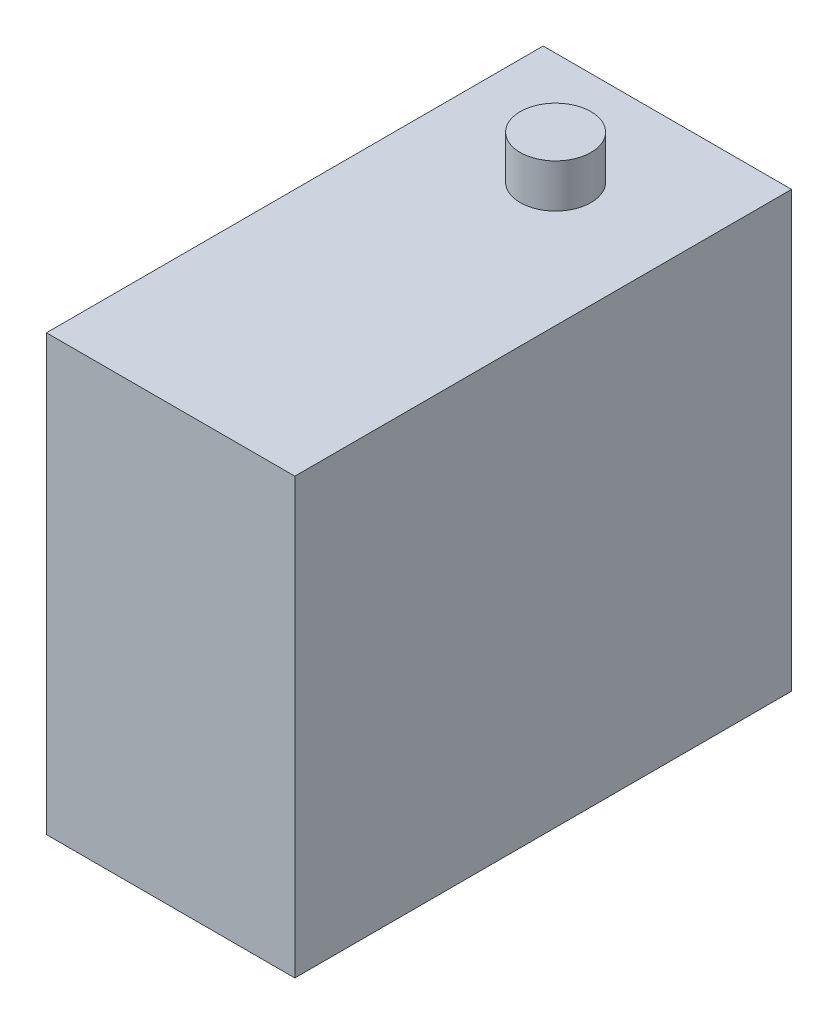
SolidWorks part; units mm, degrees
ref_plane "Front Plane" through (0, 0, 0) normal (0, 0, 1) x (1, 0, 0)
ref_plane "Top Plane" through (0, 0, 0) normal (0, 1, 0) x (1, 0, 0)
ref_plane "Right Plane" through (0, 0, 0) normal (1, 0, 0) x (0, 0, -1)
sketch "Sketch2" plane through (0, 0, 0) normal (0, 1, 0) x (1, 0, 0)
  line L1 (-10, 20) -> (10, 20)
  line L2 (-10, 20) -> (-10, -20)
  line L3 (-10, -20) -> (10, -20)
  line L4 (10, 20) -> (10, -20)
  line L5 (-10, 20) -> (10, -20) construction
  line L6 (-10, -20) -> (10, 20) construction
  point P0 (0, 0)
  dimension "D1" = 20
  dimension "D2" = 40
extrude "Boss-Extrude1" add sketch "Sketch2" along normal blind 35
sketch "Sketch3" plane through (0, 35, 0) normal (0, 1, 0) x (1, 0, 0)
  line L0 (0, 20) -> (0, 11) construction
  line L1 (10, 20) -> (-10, 20) construction
  circle A0 centre (0, 11) radius 2.85
  dimension "D2" = 5.7
  dimension "D1" = 9
extrude "Boss-Extrude2" add sketch "Sketch3" along normal blind 3.5
